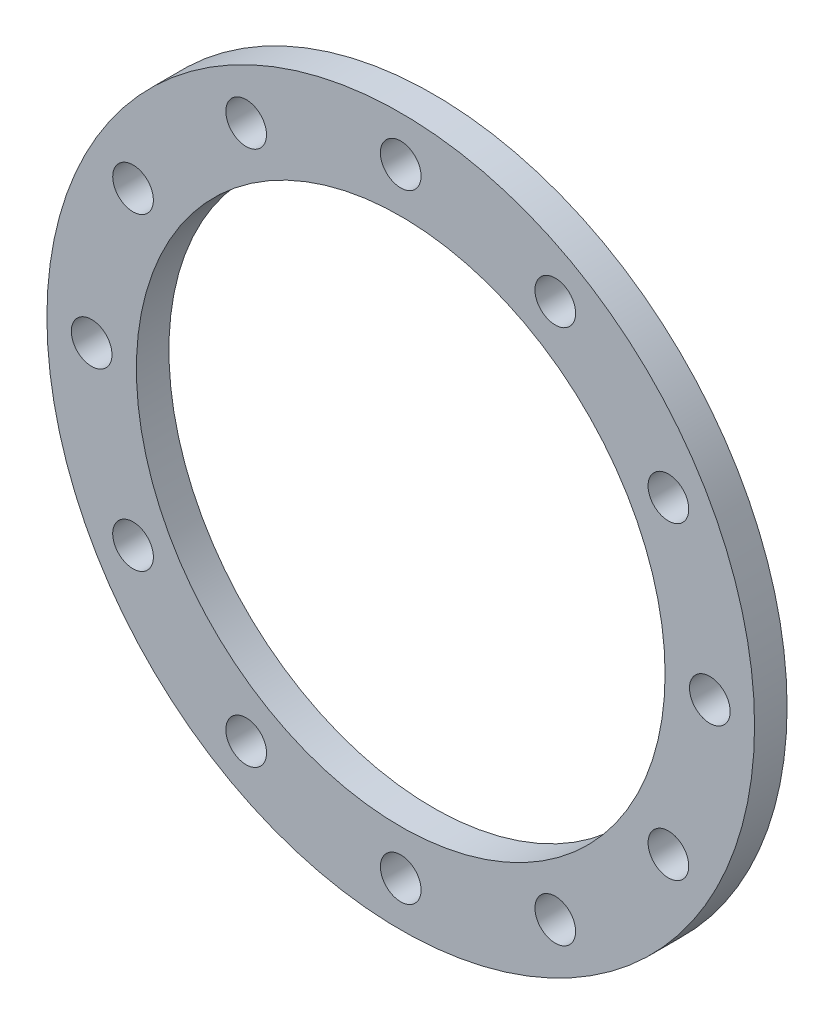
SolidWorks part; units mm, degrees
material "6061-T6 (SS)"
ref_plane "Front Plane" through (0, 0, 0) normal (0, 0, 1) x (1, 0, 0)
ref_plane "Top Plane" through (0, 0, 0) normal (0, 1, 0) x (1, 0, 0)
ref_plane "Right Plane" through (0, 0, 0) normal (1, 0, 0) x (0, 0, -1)
sketch "Sketch1" plane through (0, 0, 0) normal (0, 0, 1) x (1, 0, 0)
  circle A0 centre (0, 0) radius 43.5
  circle A1 centre (0, 0) radius 32.5
  dimension "D1" = 87
  dimension "D2" = 65
extrude "Body" add sketch "Sketch1" along normal blind 4
sketch "Sketch2" plane through (0, 0, 4) normal (0, 0, 1) x (1, 0, 0)
  line L0 (0, 0) -> (0, 43.5) construction
  circle A0 centre (0, 0) radius 43.5 construction
  circle A1 centre (0, 38) radius 2.5
  dimension "D1" = 5
  dimension "D2" = 38
extrude "Bolt Hole" cut sketch "Sketch2" against normal through all
pattern_circular "Bolt Pattern" count 12 over 360 about axis through (0, 0, 0) along (0, 0, 1) of "Bolt Hole"
equation "\"outer_diameter\"= 87.0mm"
equation "\"inner_diameter\"= 65.0mm"
equation "\"spacer_thickness\"= 4.0mm"
equation "\"bolt_diameter\"= 5.0mm"
equation "\"bolt_placement_radius\"= 38.0mm"
equation "\"num_bolts\"= 12.0"
equation "\"D1@Sketch1\"=\"outer_diameter\""
equation "\"D2@Sketch1\"=\"inner_diameter\""
equation "\"D1@Body\" = \"spacer_thickness\""
equation "\"D1@Sketch2\"=\"bolt_diameter\""
equation "\"D2@Sketch2\"=\"bolt_placement_radius\""
equation "\"D1@Bolt Pattern\"=\"num_bolts\""
